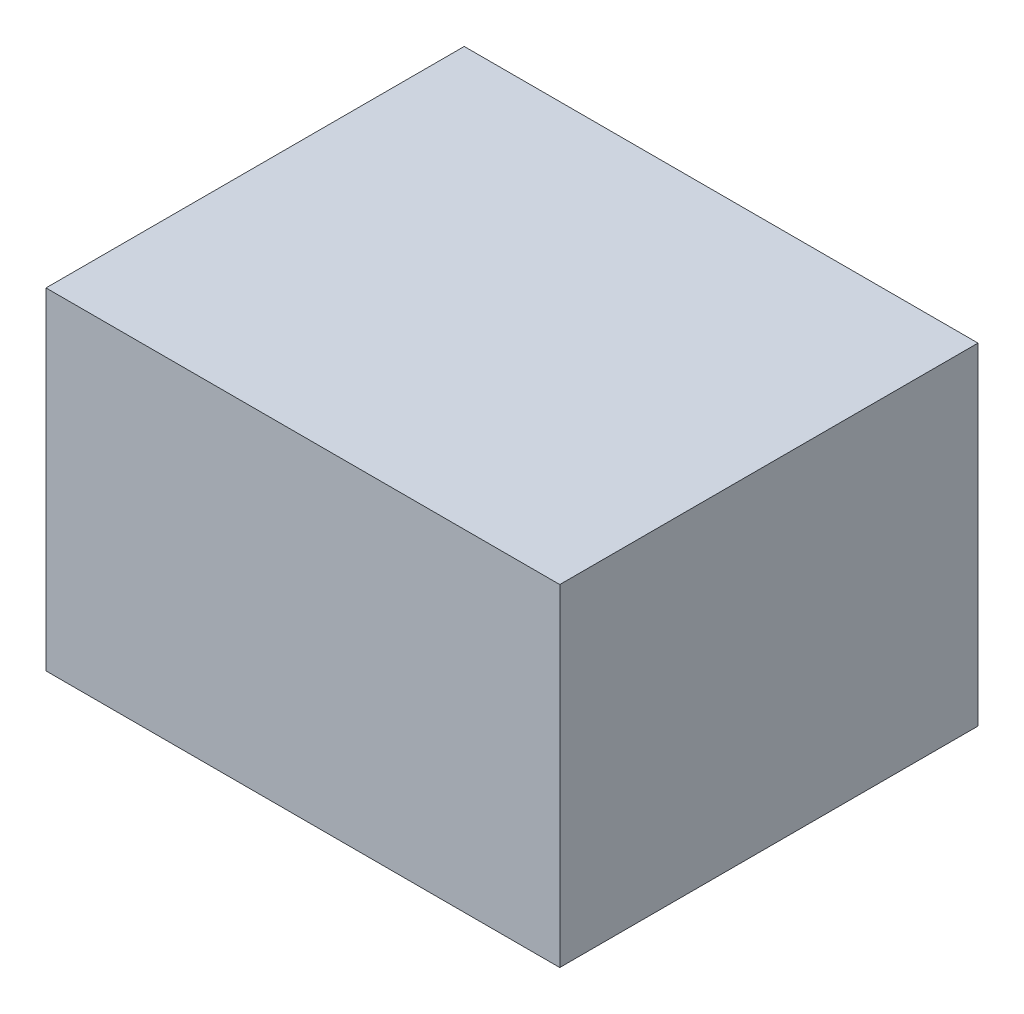
SolidWorks part; units mm, degrees
ref_plane "Front Plane" through (0, 0, 0) normal (0, 0, 1) x (1, 0, 0)
ref_plane "Top Plane" through (0, 0, 0) normal (0, 1, 0) x (1, 0, 0)
ref_plane "Right Plane" through (0, 0, 0) normal (1, 0, 0) x (0, 0, -1)
sketch "Sketch1" plane through (0, 0, 0) normal (0, 1, 0) x (1, 0, 0)
  line L1 (35.625, -29) -> (-35.625, -29)
  line L2 (35.625, -29) -> (35.625, 29)
  line L3 (35.625, 29) -> (-35.625, 29)
  line L4 (-35.625, -29) -> (-35.625, 29)
  line L5 (35.625, -29) -> (-35.625, 29) construction
  line L6 (35.625, 29) -> (-35.625, -29) construction
  point P0 (0, 0)
  dimension "D1" = 71.25
  dimension "D2" = 58
extrude "Boss-Extrude1" add sketch "Sketch1" along normal blind 46
